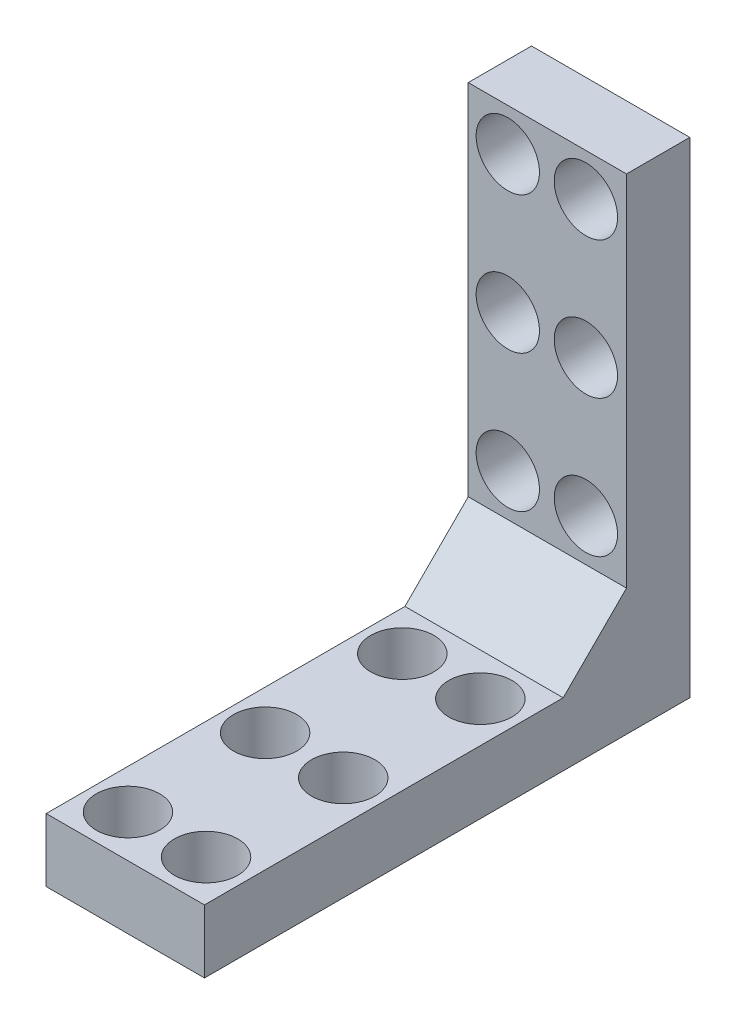
SolidWorks part; units mm, degrees
ref_plane "Front Plane" through (0, 0, 0) normal (0, 0, 1) x (1, 0, 0)
ref_plane "Top Plane" through (0, 0, 0) normal (0, 1, 0) x (1, 0, 0)
ref_plane "Right Plane" through (0, 0, 0) normal (1, 0, 0) x (0, 0, -1)
sketch "Sketch1" plane through (0, 0, 0) normal (1, 0, 0) x (0, 0, -1)
  line L0 (0, 0) -> (0, 3)
  line L1 (0, 3) -> (20, 3)
  line L2 (20, 3) -> (20, 23)
  line L3 (0, 0) -> (23, 0)
  line L4 (23, 0) -> (23, 23)
  line L5 (23, 23) -> (20, 23)
  dimension "D1" = 3
  dimension "D2" = 20
  dimension "D3" = 20
extrude "Boss-Extrude1" add sketch "Sketch1" along normal blind 7.5
chamfer "Chamfer1" distance 3 angle 45 1 edges at (3.75, 3, -20)
sketch "Sketch3" plane through (0, 0, -20) normal (0, 0, 1) x (1, 0, 0)
  line L0 (0, 23) -> (3.75, 23) construction
  line L1 (7.5, 23) -> (0, 23) construction
  line L2 (3.75, 23) -> (7.5, 23) construction
  line L3 (1.875, 23) -> (1.875, 6) construction
  line L4 (0, 6) -> (7.5, 6) construction
  line L5 (5.625, 23) -> (5.625, 6) construction
  line L6 (0, 23) -> (0, 6) construction
  circle A0 centre (1.875, 21) radius 1.5
  dimension "D1" = 3
  dimension "D2" = 2
  dimension "D3" = 1.875
extrude "Cut-Extrude1" cut sketch "Sketch3" against normal blind 10
sketch "Sketch4" plane through (0, 3, 0) normal (0, 1, 0) x (1, 0, 0)
  line L0 (0, 0) -> (3.75, 0) construction
  line L1 (7.5, 0) -> (0, 0) construction
  line L2 (3.75, 0) -> (7.5, 0) construction
  line L3 (0, 17) -> (0, 0) construction
  circle A0 centre (1.875, 2) radius 1.5
  dimension "D1" = 3
  dimension "D2" = 2
  dimension "D3" = 1.875
extrude "Cut-Extrude2" cut sketch "Sketch4" against normal blind 10
pattern_linear "LPattern1" count 2 spacing 3.7 along (1, 0, 0) count 5 spacing 3.25 along (0, -1, 0) of "Cut-Extrude1"
pattern_linear "LPattern2" count 2 spacing 3.7 along (1, 0, 0) count 5 spacing 3.25 along (0, 0, -1) of "Cut-Extrude2"
